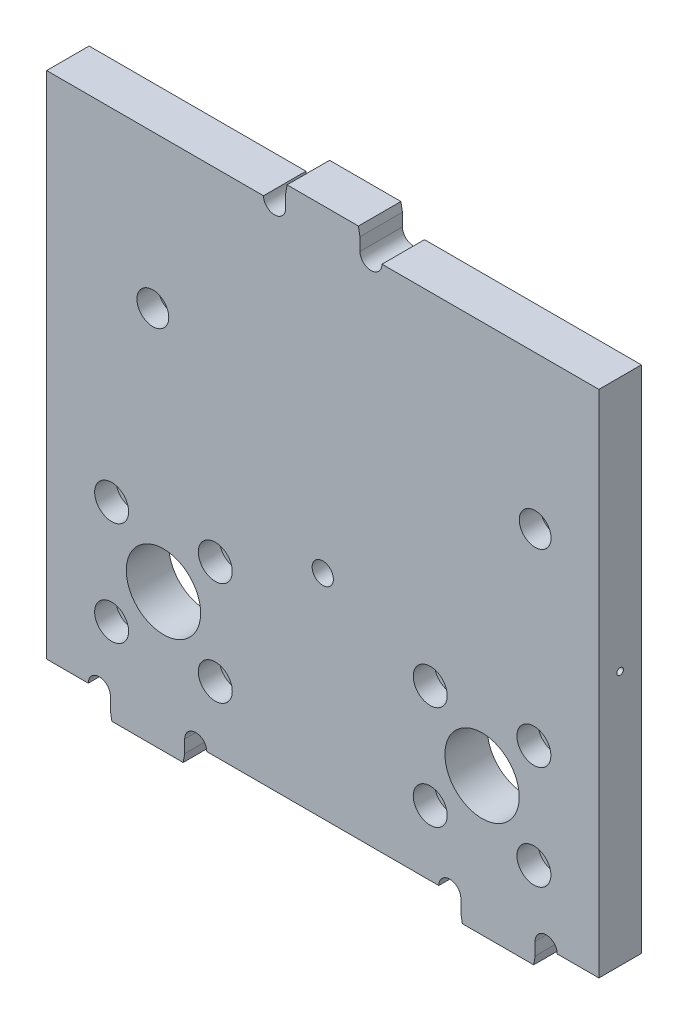
SolidWorks part; units mm, degrees
material "Delrin 2700 NC010, Low Viscosity Acetal Copolymer (SS)"
ref_plane "Front Plane" through (0, 0, 0) normal (0, 0, 1) x (1, 0, 0)
ref_plane "Top Plane" through (0, 0, 0) normal (0, 1, 0) x (1, 0, 0)
ref_plane "Right Plane" through (0, 0, 0) normal (1, 0, 0) x (0, 0, -1)
sketch "Sketch1" plane through (0, 0, 0) normal (0, 0, 1) x (1, 0, 0)
  line L1 (-82.55, -76.2) -> (82.55, -76.2)
  line L2 (-82.55, -76.2) -> (-82.55, 76.2)
  line L3 (-82.55, 76.2) -> (82.55, 76.2)
  line L4 (82.55, -76.2) -> (82.55, 76.2)
  line L5 (-82.55, -76.2) -> (82.55, 76.2) construction
  line L6 (-82.55, 76.2) -> (82.55, -76.2) construction
  point P0 (0, 0)
  dimension "D1" = 165.1
  dimension "D2" = 152.4
extrude "Boss-Extrude1" add sketch "Sketch1" along normal blind 12.7
sketch "Sketch2" plane through (0, 0, 12.7) normal (0, 0, 1) x (1, 0, 0)
  line L0 (82.55, 76.2) -> (-82.55, 76.2) construction
  line L1 (-11.1125, 76.2) -> (11.1125, 76.2)
  line L2 (-11.1125, 76.2) -> (-11.1125, 80.01)
  line L3 (-10.6646, 82.55) -> (10.6646, 82.55)
  line L4 (11.1125, 76.2) -> (11.1125, 80.01)
  line L5 (10.6646, 82.55) -> (11.1125, 80.01)
  line L6 (-10.6646, 82.55) -> (-11.1125, 80.01)
  line L7 (82.55, -76.2) -> (82.55, 76.2) construction
  point P6 (0, 82.55)
  dimension "D3" = 170
  dimension "D4" = 170
  dimension "D5" = 3.81
  dimension "D1" = 71.4375
  dimension "D2" = 6.35
extrude "Boss-Extrude2" add sketch "Sketch2" against normal up to surface (12.7 mm away) up to face at (0, 0, 0)
sketch "Sketch4" plane through (0, 0, 12.7) normal (0, 0, 1) x (1, 0, 0)
  line L0 (-11.1125, 76.2) -> (-82.55, 76.2) construction
  line L1 (-11.1125, 80.01) -> (-11.1125, 76.2) construction
  line L2 (-82.55, 76.2) -> (82.55, 76.2) construction
  line L3 (0, 82.55) -> (0, 0) construction
  line L4 (10.6646, 82.55) -> (-10.6646, 82.55) construction
  line L5 (-17.7165, 76.2) -> (-11.1125, 76.2)
  line L6 (11.1125, 76.2) -> (17.7165, 76.2)
  arc A0 (-17.7165, 76.2) -> (-11.1125, 76.2) centre (-14.4145, 76.2) ccw
  arc A1 (17.7165, 76.2) -> (11.1125, 76.2) centre (14.4145, 76.2) cw
  dimension "D1" = 6.604
  dimension "D2" = 3.302
extrude "Cut-Extrude1" cut sketch "Sketch4" against normal up to next contours A1 L6 | A0 L5
sketch "Sketch5" plane through (0, 0, 12.7) normal (0, 0, 1) x (1, 0, 0)
  line L0 (-82.55, -76.2) -> (82.55, -76.2) construction
  line L1 (63.5, -76.2) -> (41.275, -76.2)
  line L2 (63.5, -76.2) -> (63.5, -80.01)
  line L3 (63.0521, -82.55) -> (41.7229, -82.55)
  line L4 (41.275, -76.2) -> (41.275, -80.01)
  line L5 (82.55, -76.2) -> (82.55, 76.2) construction
  line L6 (41.275, -80.01) -> (41.7229, -82.55)
  line L7 (63.5, -80.01) -> (63.0521, -82.55)
  dimension "D1" = 22.225
  dimension "D2" = 6.35
  dimension "D3" = 19.05
  dimension "D4" = 170
  dimension "D5" = 170
  dimension "D6" = 3.81
extrude "Boss-Extrude3" add sketch "Sketch5" against normal up to surface (12.7 mm away) up to face at (0, 51.943, 0)
sketch "Sketch6" plane through (0, 0, 12.7) normal (0, 0, 1) x (1, 0, 0)
  line L0 (-82.55, -76.2) -> (41.275, -76.2) construction
  line L1 (82.55, -76.2) -> (0, -76.2) construction
  line L2 (34.671, -76.2) -> (41.275, -76.2)
  line L3 (52.3875, -82.55) -> (52.3875, 76.2) construction
  line L4 (41.7229, -82.55) -> (63.0521, -82.55) construction
  line L5 (82.55, 76.2) -> (17.7165, 76.2) construction
  line L6 (63.5, -76.2) -> (70.104, -76.2)
  arc A0 (41.275, -76.2) -> (34.671, -76.2) centre (37.973, -76.2) ccw
  arc A1 (63.5, -76.2) -> (70.104, -76.2) centre (66.802, -76.2) cw
  dimension "D1" = 6.604
  dimension "D2" = 3.302
extrude "Cut-Extrude2" cut sketch "Sketch6" against normal up to surface (12.7 mm away) up to face at (17.4625, 8.0998, 0)
mirror "Mirror1" about plane through (0, 0, 0) normal (1, 0, 0) of "Boss-Extrude3", "Cut-Extrude2"
sketch "Sketch7" plane through (0, 0, 12.7) normal (0, 0, 1) x (1, 0, 0)
  line L0 (-34.671, -76.2) -> (34.671, -76.2) construction
  line L1 (-82.55, 76.2) -> (-82.55, -76.2) construction
  line L2 (82.55, -76.2) -> (82.55, 76.2) construction
  circle A0 centre (-47.625, -41.275) radius 11.1125
  circle A1 centre (47.625, -41.275) radius 11.1125
  dimension "D4" = 22.225
  dimension "D5" = 22.225
  dimension "D1" = 34.925
  dimension "D2" = 34.925
  dimension "D3" = 34.925
extrude "Cut-Extrude3" cut sketch "Sketch7" against normal up to surface (12.7 mm away) up to face at (0, -22.2613, 0)
sketch "Sketch9" plane through (0, 0, 12.7) normal (0, 0, 1) x (1, 0, 0)
  circle A0 centre (-47.625, -41.275) radius 21.9118 construction
  point P3 (-32.131, -25.781)
  point P4 (-63.119, -25.781)
  point P5 (-63.119, -56.769)
  point P6 (-32.131, -56.769)
  dimension "D1" = 43.8236
  dimension "D2" = 15.494
hole_wizard "M3 Clearance Hole1" positions "Sketch10" profile "Sketch11" hole size "M3" standard "ANSI Metric" end condition through all
sketch "Sketch10" plane through (0, 0, 12.7) normal (0, 0, 1) x (1, 0, 0)
  point P0 (-63.119, -25.781)
  point P3 (-32.131, -25.781)
  point P6 (-32.131, -56.769)
  point P9 (-63.119, -56.769)
sketch "Sketch11" plane through (-63.119, -25.781, 12.7) normal (1, 0, 0) x (0, -1, 0)
  line L0 (0, 0) -> (0, 12.7)
  line L1 (0, 12.7) -> (1.7, 12.7)
  line L2 (1.7, 12.7) -> (1.7, 0)
  line L5 (1.7, 0) -> (0, 0)
  line L11 (0, -6.35) -> (0, 107.95) construction
  dimension "Thru Hole Dia." = 3.4
  dimension "Thru Hole Depth" = 12.7
mirror "Mirror2" about plane through (0, 0, 0) normal (1, 0, 0) of "M3 Clearance Hole1"
sketch "Sketch13" plane through (0, 0, 12.7) normal (0, 0, 1) x (1, 0, 0)
  circle A1 centre (-47.625, -41.275) radius 55.5625 construction
  circle A2 centre (47.625, -41.275) radius 55.5625 construction
  circle A3 centre (0, -12.6559) radius 3.175
  dimension "D1" = 111.125
  dimension "D2" = 111.125
  dimension "D3" = 6.35
sketch "Sketch14" plane through (0, 0, 12.7) normal (0, 0, 1) x (1, 0, 0)
  line L1 (-82.55, 76.2) -> (-82.55, -76.2) construction
  circle A0 centre (0, -12.6559) radius 66.675 construction
  circle A1 centre (-50.8, 30.5287) radius 4.7625
  circle A2 centre (-50.8, 30.5287) radius 114.3 construction
  circle A3 centre (63.5, 30.5287) radius 4.7625
  circle A4 centre (47.625, -41.275) radius 55.5625 construction
  circle A5 centre (-47.625, -41.275) radius 55.5625 construction
  point P8 (0, 0)
  point P11 (8.7418, 16.1034)
  dimension "D1" = 133.35
  dimension "D2" = 9.525
  dimension "D3" = 228.6
  dimension "D4" = 9.525
  dimension "D5" = 31.75
extrude "Cut-Extrude5" cut sketch "Sketch14" against normal blind 6.35 contours A1 | A3
extrude "Cut-Extrude7" cut sketch "Sketch13" against normal blind 6.35 contours A3
hole_wizard "#8 Clearance Hole1" positions "Sketch16" profile "Sketch17" hole size "#8" standard "ANSI Inch" end condition through all
sketch "Sketch16" plane through (0, 0, 12.7) normal (0, 0, 1) x (1, 0, 0)
  point P0 (0, -12.6559)
  point P3 (63.5, 30.5287)
  point P6 (-50.8, 30.5287)
sketch "Sketch17" plane through (0, -12.6559, 12.7) normal (1, 0, 0) x (0, -1, 0)
  line L0 (0, 0) -> (0, 12.7)
  line L1 (0, 12.7) -> (2.2479, 12.7)
  line L2 (2.2479, 12.7) -> (2.2479, 0)
  line L5 (2.2479, 0) -> (0, 0)
  line L11 (0, -6.35) -> (0, 107.95) construction
  dimension "Thru Hole Dia." = 4.4958
  dimension "Thru Hole Depth" = 12.7
sketch "Sketch18" plane through (0, 0, 12.7) normal (0, 0, 1) x (1, 0, 0)
  line L0 (-47.625, -30.1625) -> (-47.625, -52.3875) construction
  line L1 (-58.7375, -41.275) -> (-36.5125, -41.275) construction
  line L2 (0, 0) -> (0, -76.2) construction
  line L3 (-34.671, -76.2) -> (34.671, -76.2) construction
  circle A0 centre (-63.119, -25.781) radius 5.08
  circle A1 centre (-47.625, -41.275) radius 11.1125 construction
  circle A2 centre (-63.119, -56.769) radius 5.08
  circle A3 centre (-32.131, -56.769) radius 5.08
  circle A4 centre (-32.131, -25.781) radius 5.08
  circle A5 centre (32.131, -25.781) radius 5.08
  circle A6 centre (32.131, -56.769) radius 5.08
  circle A7 centre (63.119, -56.769) radius 5.08
  circle A8 centre (63.119, -25.781) radius 5.08
  dimension "D1" = 10.16
extrude "Cut-Extrude8" cut sketch "Sketch18" against normal blind 6.35
sketch "Sketch20" plane through (82.55, 0, 0) normal (1, 0, 0) x (0, 0, -1)
  line L1 (-12.7, -76.2) -> (0, -76.2) construction
  circle A0 centre (-6.35, 0) radius 0.9919
  point P0 (-6.35, 0)
  point P2 (-6.35, 0)
  point P7 (-6.35, -76.2)
  dimension "D2" = 1.9837
  dimension "D1" = 76.2
extrude "Cut-Extrude9" cut sketch "Sketch20" against normal blind 25.4
mirror "Mirror3" about plane through (0, 0, 0) normal (1, 0, 0) of "Cut-Extrude9"
equation "\"D4@Sketch2\"=\"D3@Sketch2\""
equation "\"D2@Sketch4\"=\"D1@Sketch4\"/2"
equation "\"D2@Sketch6\"=\"D1@Sketch6\"/2"
equation "\"D3@Sketch7\"=\"D2@Sketch7\""
equation "\"D5@Sketch7\"=\"D4@Sketch7\""
equation "\"D2@Sketch13\"=\"D1@Sketch13\""
equation "\"D4@Sketch14\"=\"D2@Sketch14\""
